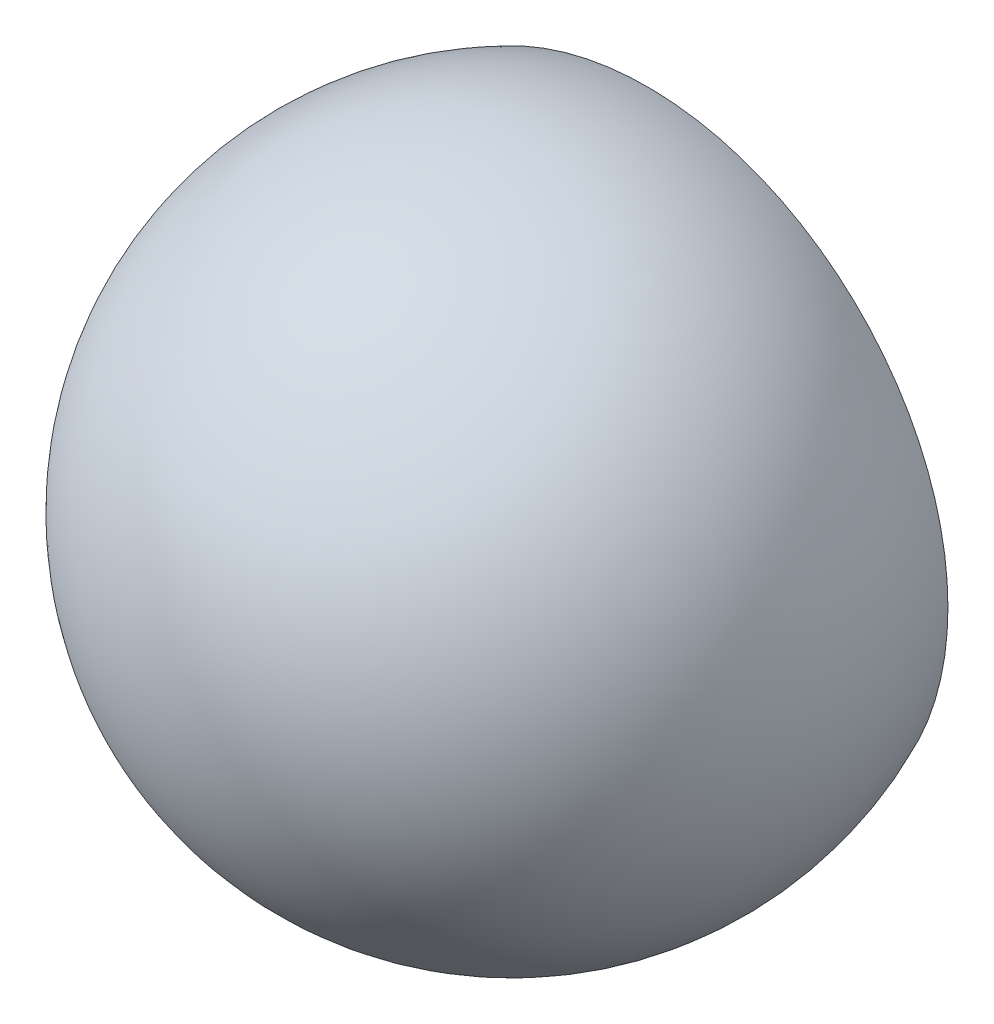
SolidWorks part; units mm, degrees
ref_plane "Front Plane" through (0, 0, 0) normal (0, 0, 1) x (1, 0, 0)
ref_plane "Top Plane" through (0, 0, 0) normal (0, 1, 0) x (1, 0, 0)
ref_plane "Right Plane" through (0, 0, 0) normal (1, 0, 0) x (0, 0, -1)
sketch "Sketch1" plane through (0, 0, 0) normal (0, 0, 1) x (1, 0, 0)
  line L0 (0, 4.87) -> (0, -4.87)
  arc A0 (0, 4.87) -> (0, -4.87) centre (0, 0) ccw
  dimension "D1" = 9.74
revolve "Revolve1" add sketch "Sketch1" angle 360 about L0
sketch "Sketch2" plane through (0, 0, 0) normal (1, 0, 0) x (0, 0, -1)
  line L0 (2, 0) -> (0, 0) construction
  line L2 (5, -4.87) -> (2, -4.87)
  line L3 (5, -4.87) -> (5, 4.87)
  line L4 (5, 4.87) -> (2, 4.87)
  line L8 (2, 4.87) -> (2, -4.87)
  dimension "D1" = 9.74
  dimension "D2" = 3
extrude "Cut-Extrude1" cut sketch "Sketch2" against normal through all both and the other way through all
